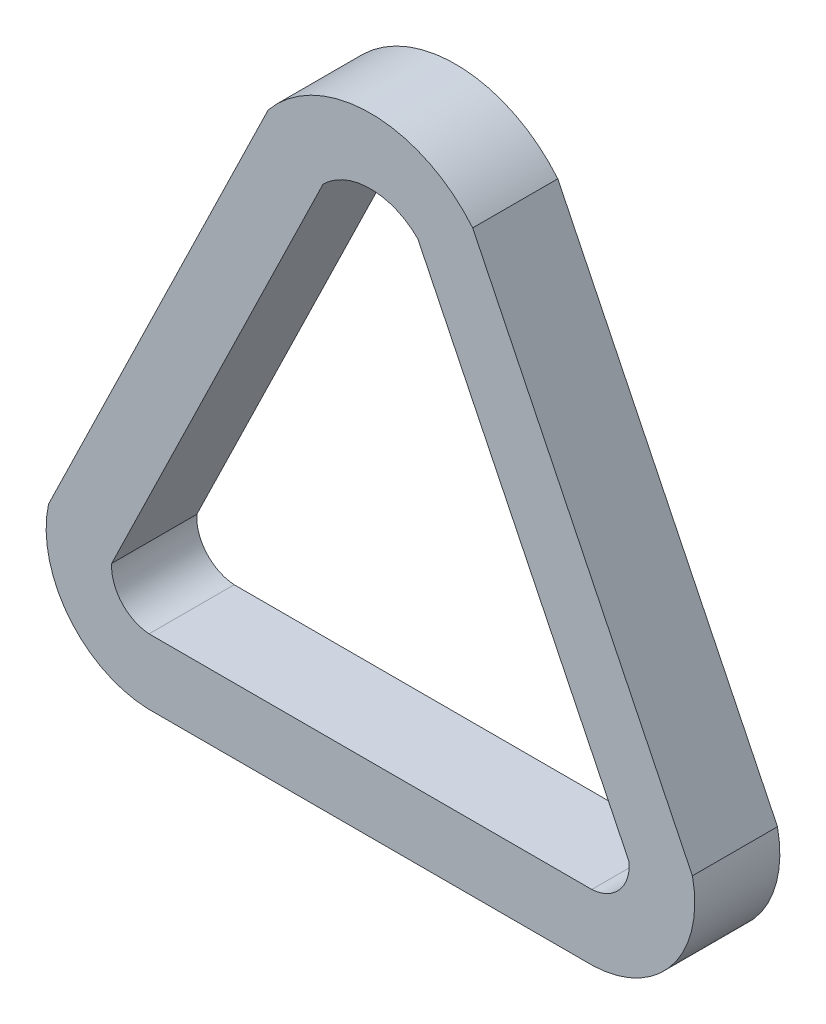
SolidWorks part; units mm, degrees
ref_plane "Plano frontal" through (0, 0, 0) normal (0, 0, 1) x (1, 0, 0)
ref_plane "Plano superior" through (0, 0, 0) normal (0, 1, 0) x (1, 0, 0)
ref_plane "Plano direito" through (0, 0, 0) normal (1, 0, 0) x (0, 0, -1)
sketch "Esboço1" plane through (0, 0, 0) normal (0, 0, 1) x (1, 0, 0)
  line L0 (0, -44.0993) -> (0, -39.8757) construction
  line L2 (-7.2326, 32.9192) -> (-39.5307, -33.4161)
  line L4 (-33.8164, -39.8757) -> (33.8164, -39.8757)
  line L6 (7.2326, 32.9192) -> (39.5307, -33.4161)
  line L7 (0, 35.915) -> (0, 44.0993) construction
  line L8 (15.6159, 38.5448) -> (49.1789, -30.3884)
  line L9 (-34.0494, -49.8757) -> (34.0494, -49.8757)
  line L10 (-15.6159, 38.5448) -> (-49.1789, -30.3884)
  arc A0 (-7.2326, 32.9192) -> (7.2326, 32.9192) centre (0, 25.6865) cw
  arc A1 (-39.5307, -33.4161) -> (-33.8164, -39.8757) centre (-33.4438, -33.7887) ccw
  arc A2 (33.8164, -39.8757) -> (39.5307, -33.4161) centre (33.4438, -33.7887) ccw
  arc A3 (-15.6159, 38.5448) -> (15.6159, 38.5448) centre (0, 25.6865) cw
  arc A4 (34.0494, -49.8757) -> (49.1789, -30.3884) centre (33.4438, -33.7887) ccw
  arc A5 (-49.1789, -30.3884) -> (-34.0494, -49.8757) centre (-33.4438, -33.7887) ccw
  point P4 (0, 0)
  point P11 (0, -39.8757)
  point P13 (0, 32.9192)
  dimension "D1" = 10
extrude "Ressalto-extrusão1" add sketch "Esboço1" along normal blind 13
